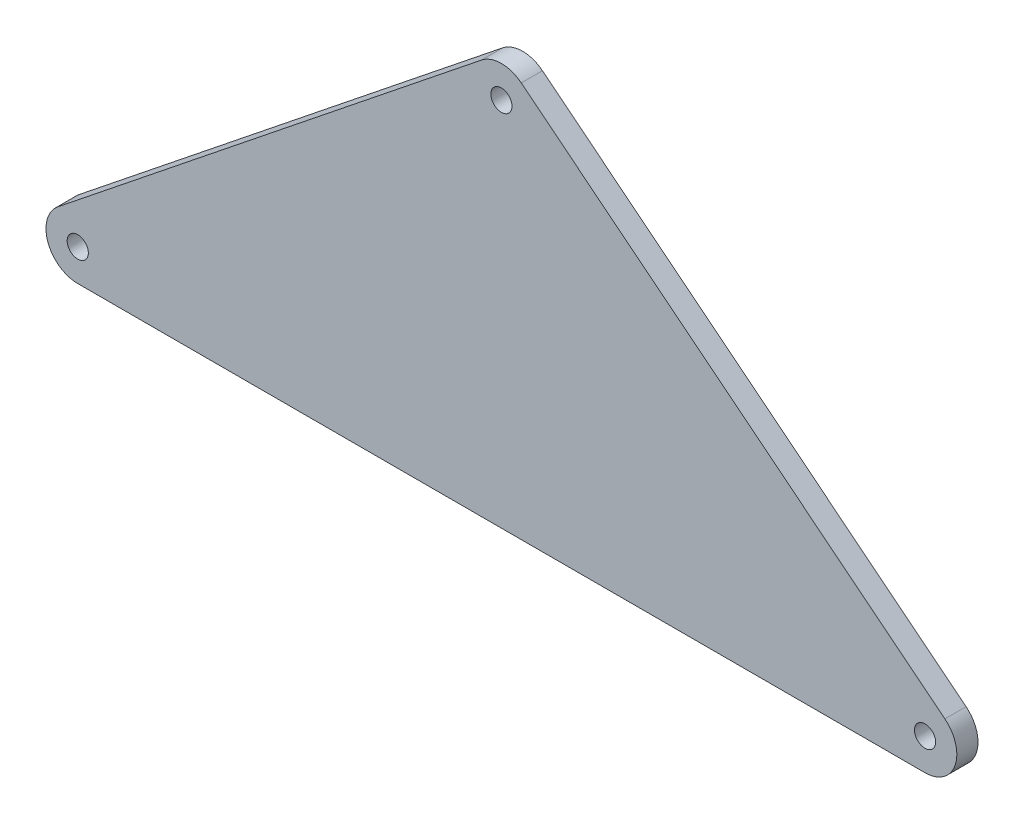
SolidWorks part; units mm, degrees
material "Commercially Pure Grade 2 Textured (SS)"
ref_plane "Front Plane" through (0, 0, 0) normal (0, 0, 1) x (1, 0, 0)
ref_plane "Top Plane" through (0, 0, 0) normal (0, 1, 0) x (1, 0, 0)
ref_plane "Right Plane" through (0, 0, 0) normal (1, 0, 0) x (0, 0, -1)
sketch "Sketch1" plane through (0, 0, 0) normal (0, 0, 1) x (1, 0, 0)
  line L0 (0, 0) -> (127, 0) construction
  line L1 (63.5, 0) -> (63.5, 50.8) construction
  line L2 (60.5249, 54.5189) -> (-2.9751, 3.7189)
  line L3 (66.4751, 54.5189) -> (129.9751, 3.7189)
  line L4 (0, -4.7625) -> (127, -4.7625)
  circle A0 centre (0, 0) radius 1.5875
  circle A1 centre (127, 0) radius 1.5875
  circle A2 centre (63.5, 50.8) radius 1.5875
  circle A3 centre (0, 0) radius 4.7625
  circle A4 centre (63.5, 50.8) radius 4.7625
  circle A5 centre (127, 0) radius 4.7625
  dimension "D1" = 3.175
  dimension "D4" = 9.525
  dimension "D2" = 127
  dimension "D3" = 50.8
extrude "Boss-Extrude1" add sketch "Sketch1" along normal blind 3.175 contours A5 L3 A4 L2 A3 L4 | A3 A0 | A4 A2 | A5 A1
